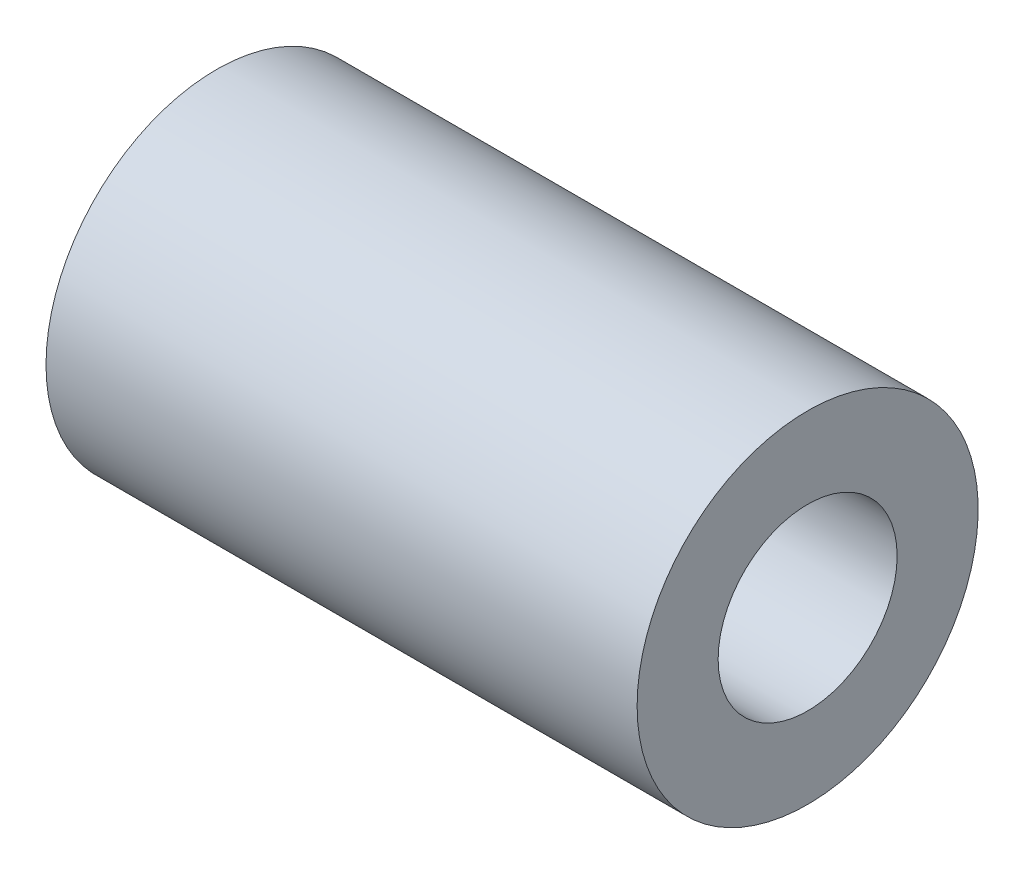
SolidWorks part; units mm, degrees
material "Plain Carbon Steel"
ref_plane "Front Plane" through (0, 0, 0) normal (0, 0, 1) x (1, 0, 0)
ref_plane "Top Plane" through (0, 0, 0) normal (0, 1, 0) x (1, 0, 0)
ref_plane "Right Plane" through (0, 0, 0) normal (1, 0, 0) x (0, 0, -1)
sketch "Sketch1" plane through (0, 0, 0) normal (1, 0, 0) x (0, 0, -1)
  circle A0 centre (0, 0) radius 15
  circle A1 centre (0, 0) radius 7.874
  dimension "D1" = 15.748
  dimension "D2" = 30
extrude "Boss-Extrude1" add sketch "Sketch1" along normal blind 52
